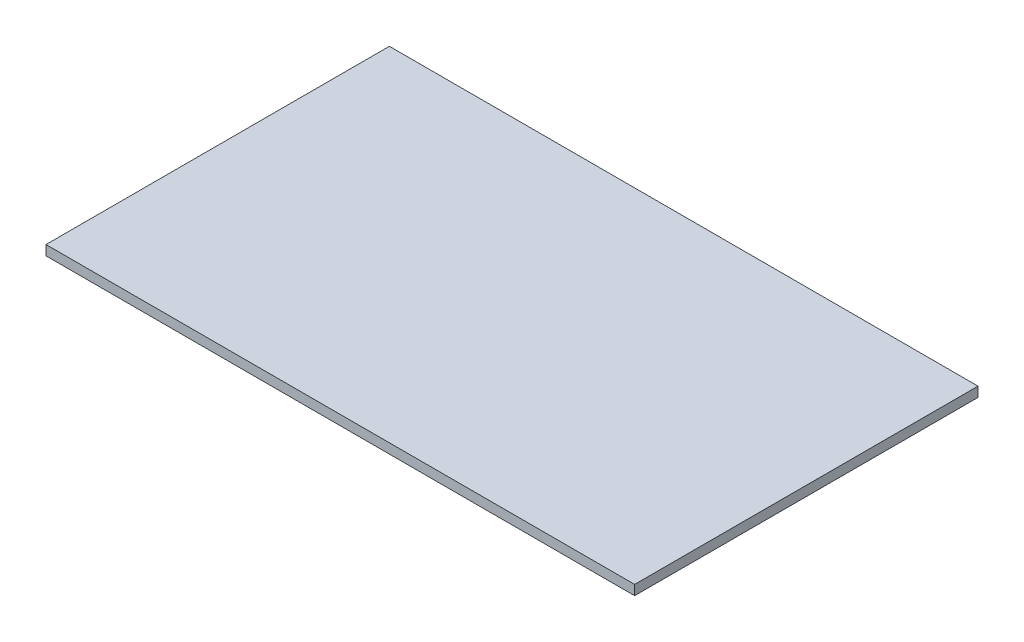
SolidWorks part; units mm, degrees
ref_plane "Front Plane" through (0, 0, 0) normal (0, 0, 1) x (1, 0, 0)
ref_plane "Top Plane" through (0, 0, 0) normal (0, 1, 0) x (1, 0, 0)
ref_plane "Right Plane" through (0, 0, 0) normal (1, 0, 0) x (0, 0, -1)
sketch "Sketch1" plane through (0, 0, 0) normal (0, 1, 0) x (1, 0, 0)
  line L1 (-300, -175) -> (300, -175)
  line L2 (-300, -175) -> (-300, 175)
  line L3 (-300, 175) -> (300, 175)
  line L4 (300, -175) -> (300, 175)
  line L5 (-300, -175) -> (300, 175) construction
  line L6 (-300, 175) -> (300, -175) construction
  point P0 (0, 0)
  dimension "D1" = 600
  dimension "D2" = 350
extrude "Boss-Extrude1" add sketch "Sketch1" along normal blind 10
